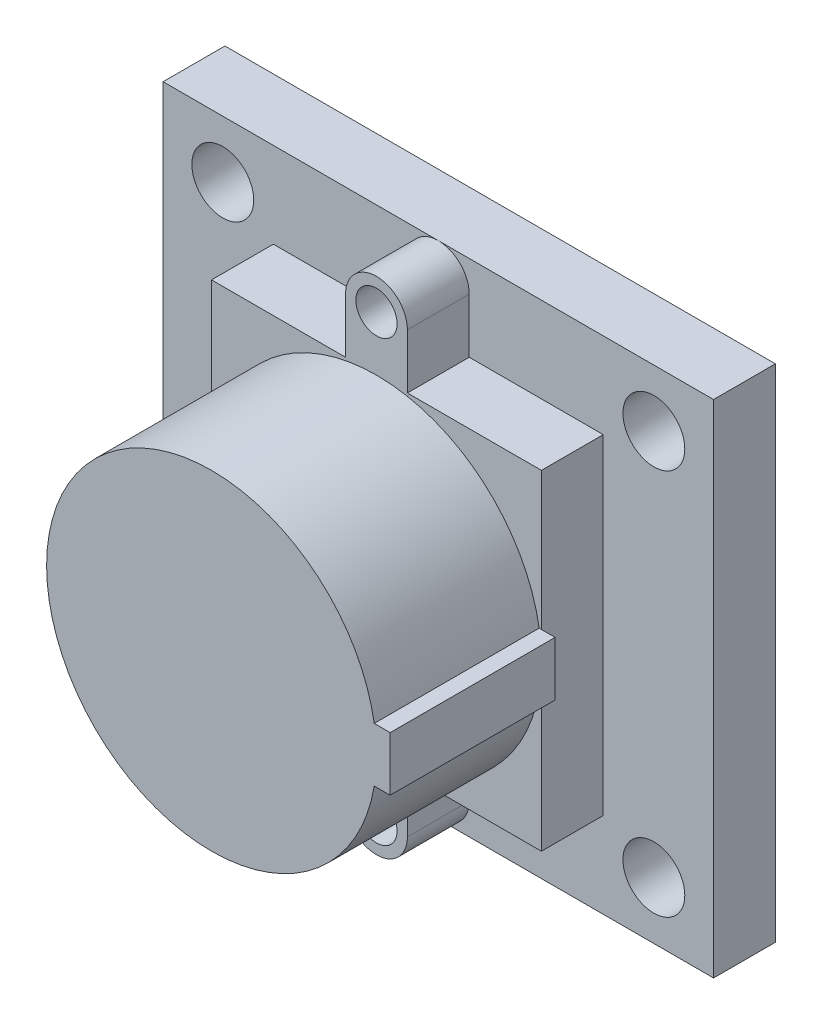
SolidWorks part; units mm, degrees
ref_plane "前视基准面" through (0, 0, 0) normal (0, 0, 1) x (1, 0, 0)
ref_plane "上视基准面" through (0, 0, 0) normal (0, 1, 0) x (1, 0, 0)
ref_plane "右视基准面" through (0, 0, 0) normal (1, 0, 0) x (0, 0, -1)
sketch "草图1" plane through (0, 0, 0) normal (0, 0, 1) x (1, 0, 0)
  line L0 (6.6944, 0) -> (33.3944, 0) construction
  line L1 (6.6944, 12.15) -> (33.3944, 12.15)
  line L2 (6.6944, 12.15) -> (6.6944, -12.15)
  line L3 (6.6944, -12.15) -> (33.3944, -12.15)
  line L4 (33.3944, 12.15) -> (33.3944, -12.15)
  line L7 (20.0444, 12.15) -> (20.0444, -12.15) construction
  circle A0 centre (30.4994, 9.375) radius 1.5
  circle A1 centre (9.5894, 9.375) radius 1.5
  circle A2 centre (30.4994, -9.375) radius 1.5
  circle A3 centre (9.5894, -9.375) radius 1.5
  point P0 (0, 0)
  dimension "D1" = 3
  dimension "D2" = 3
  dimension "D3" = 3
  dimension "D4" = 3
  dimension "D5" = 18.75
  dimension "D6" = 20.91
  dimension "D7" = 26.7
  dimension "D8" = 24.3
extrude "凸台-拉伸1" add sketch "草图1" along normal blind 3
sketch "草图2" plane through (0, 0, 3) normal (0, 0, 1) x (1, 0, 0)
  line L0 (33.3944, 0) -> (6.6944, 0) construction
  line L1 (33.3944, -12.15) -> (33.3944, 12.15) construction
  line L2 (6.6944, 12.15) -> (6.6944, -12.15) construction
  line L3 (20.0444, 12.15) -> (20.0444, -12.15) construction
  line L4 (33.3944, 12.15) -> (6.6944, 12.15) construction
  line L5 (6.6944, -12.15) -> (33.3944, -12.15) construction
  line L7 (12.0444, 8) -> (18.5444, 8)
  line L8 (12.0444, 8) -> (12.0444, 1.75)
  line L9 (12.0444, -8) -> (18.5444, -8)
  line L10 (28.0444, 8) -> (28.0444, 1.75)
  line L11 (12.0444, 8) -> (28.0444, -8) construction
  line L12 (12.0444, -8) -> (28.0444, 8) construction
  line L16 (12.0444, -1.75) -> (12.0444, -8)
  line L17 (28.0444, -1.75) -> (28.0444, -8)
  line L18 (21.5444, -10.65) -> (21.5444, -8)
  line L19 (18.5444, -10.65) -> (18.5444, -8)
  line L20 (21.5444, 10.65) -> (21.5444, 8)
  line L21 (18.5444, 10.65) -> (18.5444, 8)
  line L22 (28.0444, 1.75) -> (28.0444, -1.75)
  line L23 (12.0444, 1.75) -> (12.0444, -1.75)
  line L24 (21.5444, 8) -> (28.0444, 8)
  line L25 (21.5444, -8) -> (28.0444, -8)
  arc A4 (21.5444, 10.65) -> (18.5444, 10.65) centre (20.0444, 10.65) ccw
  circle A5 centre (20.0444, 10.65) radius 1
  arc A6 (18.5444, -10.65) -> (21.5444, -10.65) centre (20.0444, -10.65) ccw
  circle A7 centre (20.0444, -10.65) radius 1
  point P12 (20.0444, 0)
  dimension "D6" = 3
  dimension "D7" = 2
  dimension "D8" = 3
  dimension "D9" = 2
  dimension "D1" = 16
extrude "凸台-拉伸2" add sketch "草图2" along normal blind 3
sketch "草图3" plane through (0, 0, 6) normal (0, 0, 1) x (1, 0, 0)
  line L0 (20.0444, 12.15) -> (20.0444, -12.15) construction
  line L2 (27.9355, 1.3153) -> (28.7091, 1.3153)
  line L4 (27.9355, -1.3153) -> (28.7091, -1.3153)
  line L5 (28.7091, 1.3153) -> (28.7091, -1.3153)
  arc A0 (21.5444, 10.65) -> (18.5444, 10.65) centre (20.0444, 10.65) ccw construction
  arc A1 (18.5444, -10.65) -> (21.5444, -10.65) centre (20.0444, -10.65) ccw construction
  arc A2 (27.9355, 1.3153) -> (27.9355, -1.3153) centre (20.0444, 0) ccw
  point P10 (28.0444, 0)
extrude "凸台-拉伸3" add sketch "草图3" along normal blind 8
